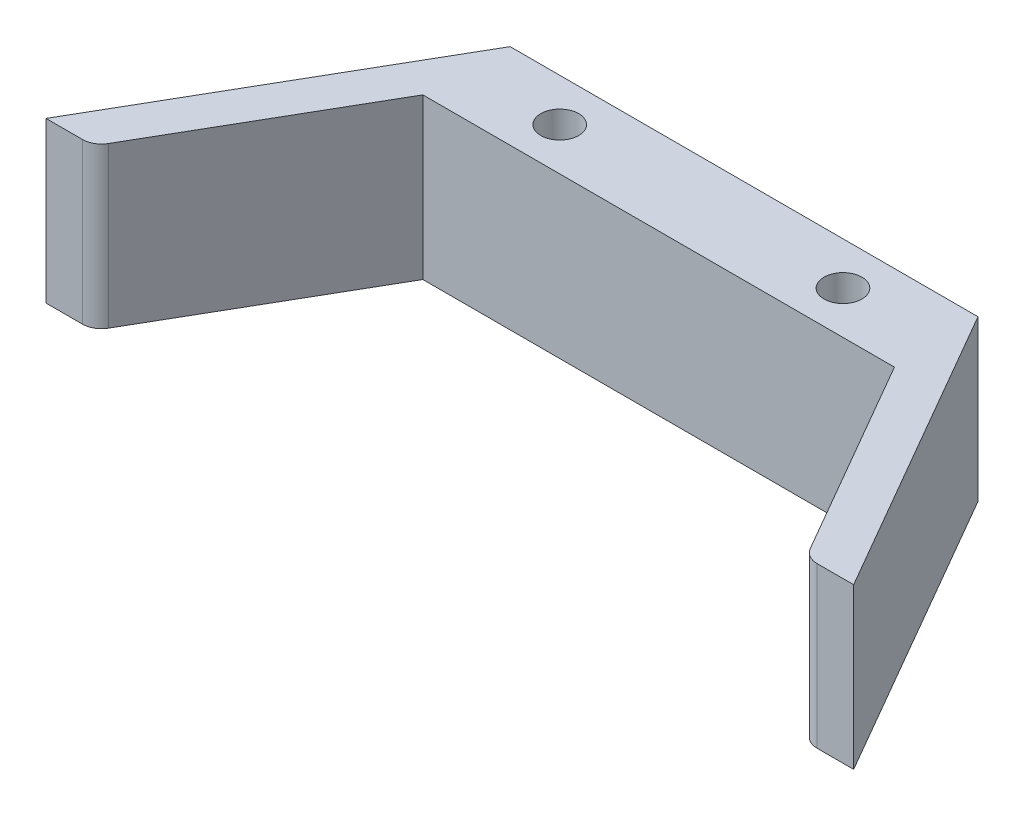
SolidWorks part; units mm, degrees
ref_plane "Front Plane" through (0, 0, 0) normal (0, 0, 1) x (1, 0, 0)
ref_plane "Top Plane" through (0, 0, 0) normal (0, 1, 0) x (1, 0, 0)
ref_plane "Right Plane" through (0, 0, 0) normal (1, 0, 0) x (0, 0, -1)
sketch "Sketch1" plane through (0, 0, 0) normal (0, 1, 0) x (1, 0, 0)
  line L0 (-29.8412, 0) -> (29.8412, 0)
  line L1 (29.8412, 0) -> (24.645, 9)
  line L2 (24.645, 9) -> (-24.645, 9)
  line L3 (-24.645, 9) -> (-29.8412, 0)
  line L4 (0, 20.8405) -> (0, -18.5494) construction
  line L5 (29.8412, 0) -> (42.5429, -22)
  line L6 (24.6436, 9.0024) -> (47.1603, -29.9976) construction
  line L7 (42.5429, -22) -> (38.6976, -22)
  line L8 (36.9655, -21) -> (24.8412, 0)
  line L9 (42.5429, -22) -> (29.8412, 0)
  line L10 (-36.9655, -21) -> (-24.8412, 0)
  line L11 (-42.5429, -22) -> (-38.6976, -22)
  line L12 (-29.8412, 0) -> (-42.5429, -22)
  circle A0 centre (-14.92, 4.5) radius 2
  circle A1 centre (14.92, 4.5) radius 2
  arc A2 (36.9655, -21) -> (38.6976, -22) centre (38.6976, -20) ccw
  arc A3 (-36.9655, -21) -> (-38.6976, -22) centre (-38.6976, -20) cw
  point P4 (0, 0)
  point P19 (37.5429, -22)
  dimension "D6" = 4
  dimension "D10" = 2
  dimension "D1" = 60
  dimension "D2" = 60
  dimension "D3" = 49.29
  dimension "D4" = 9
  dimension "D5" = 4.5
  dimension "D7" = 14.92
  dimension "D8" = 5
  dimension "D9" = 22
extrude "Boss-Extrude1" add sketch "Sketch1" along normal blind 16.85 contours L4 L2 L3 L0 A0 | L2 L4 L0 L1 A1 | A3 L10 L0 L12 L11 | L8 A2 L7 L5 L0
